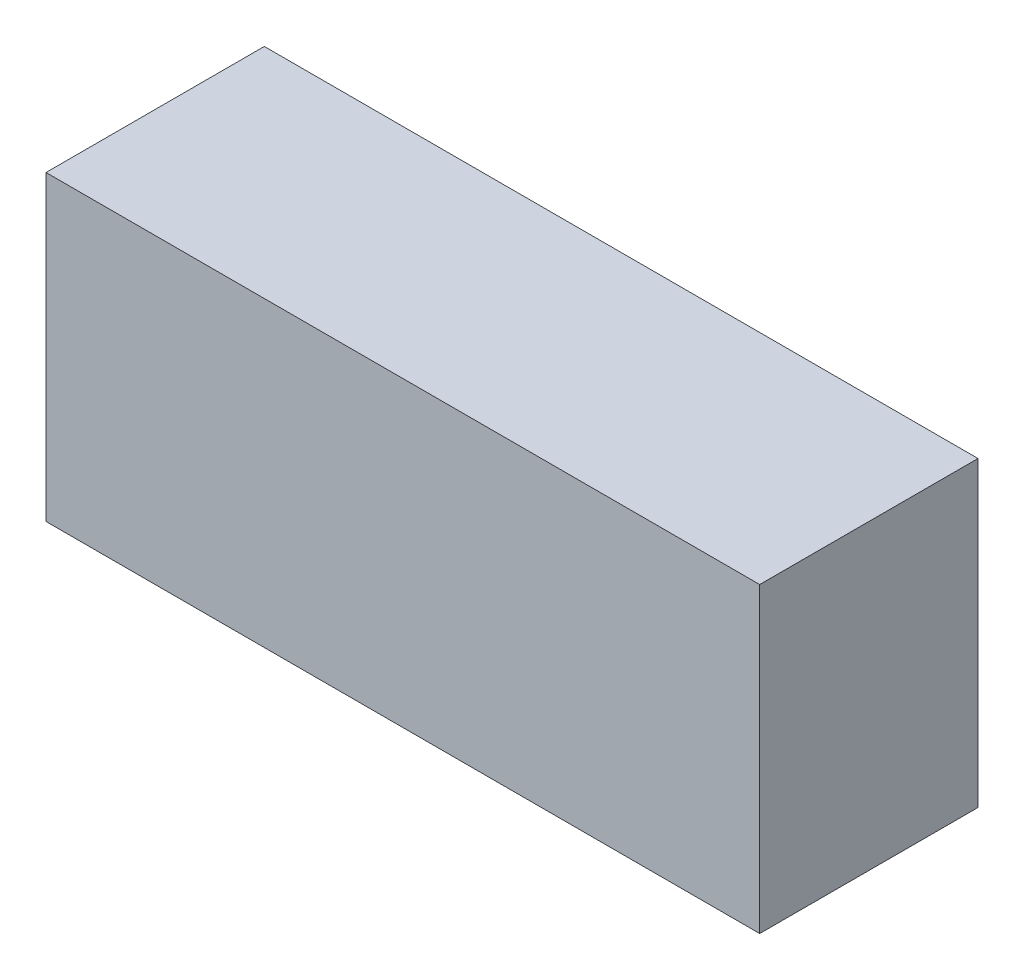
SolidWorks part; units mm, degrees
ref_plane "前视基准面" through (0, 0, 0) normal (0, 0, 1) x (1, 0, 0)
ref_plane "上视基准面" through (0, 0, 0) normal (0, 1, 0) x (1, 0, 0)
ref_plane "右视基准面" through (0, 0, 0) normal (1, 0, 0) x (0, 0, -1)
sketch "草图1" plane through (0, 0, 0) normal (0, 0, 1) x (1, 0, 0)
  line L0 (2.125, 0.9) -> (2.125, -0.9)
  line L1 (2.125, -0.9) -> (-2.125, -0.9)
  line L2 (-2.125, -0.9) -> (-2.125, 0.9)
  line L3 (-2.125, 0.9) -> (2.125, 0.9)
extrude "Component_Outline" add sketch "草图1" along normal blind 1.3 separate body
sketch3d "3D草图1"
  line L0 (0, 0, 0) -> (1, 0, 0)
  line L1 (0, 0, 0) -> (0, 1, 0)
  line L2 (0, 0, 0) -> (0, 0, 1)
  point P0 (0, 0, 0)
